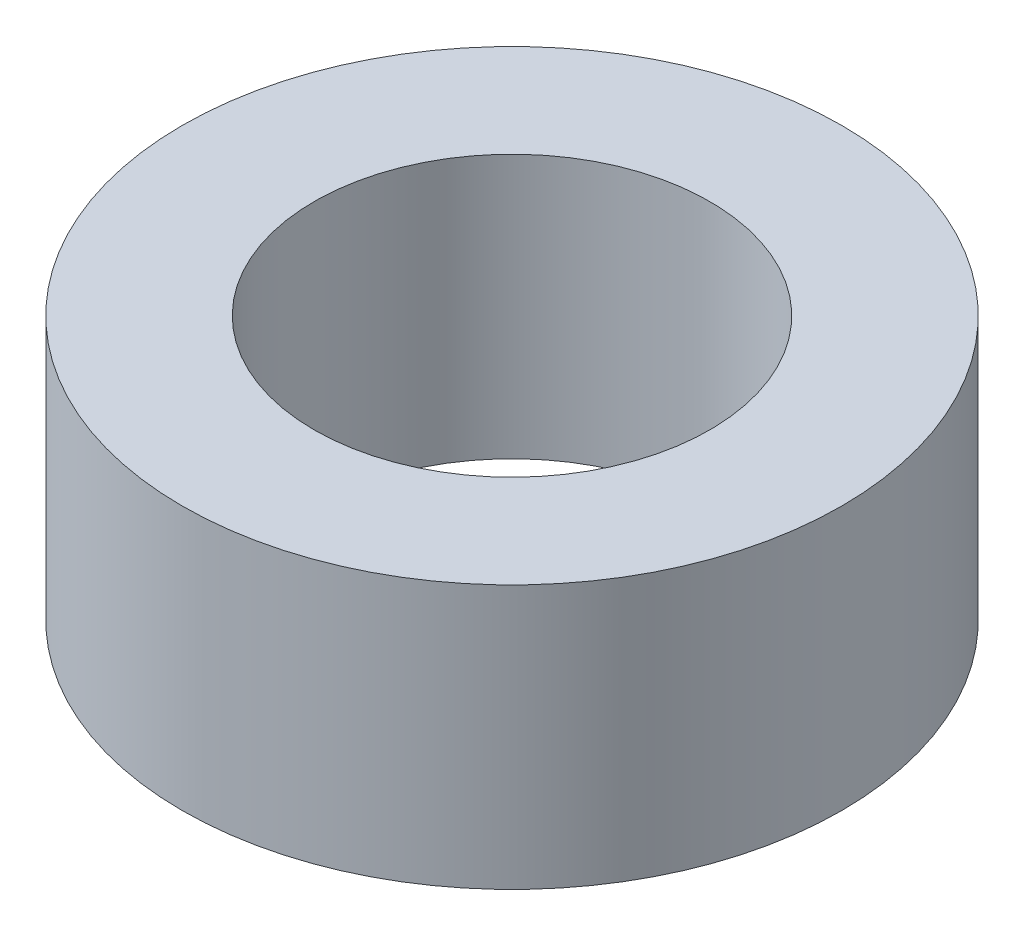
SolidWorks part; units mm, degrees
ref_plane "Front Plane" through (0, 0, 0) normal (0, 0, 1) x (1, 0, 0)
ref_plane "Top Plane" through (0, 0, 0) normal (0, 1, 0) x (1, 0, 0)
ref_plane "Right Plane" through (0, 0, 0) normal (1, 0, 0) x (0, 0, -1)
sketch "Sketch2" plane through (0, 0, 0) normal (0, 1, 0) x (1, 0, 0)
  circle A0 centre (0, 0) radius 10
  dimension "D1" = 20
extrude "Boss-Extrude1" add sketch "Sketch2" along normal blind 8
sketch "Sketch3" plane through (0, 8, 0) normal (0, 1, 0) x (1, 0, 0)
  circle A0 centre (0, 0) radius 6
  dimension "D1" = 12
extrude "Cut-Extrude1" cut sketch "Sketch3" against normal through all
